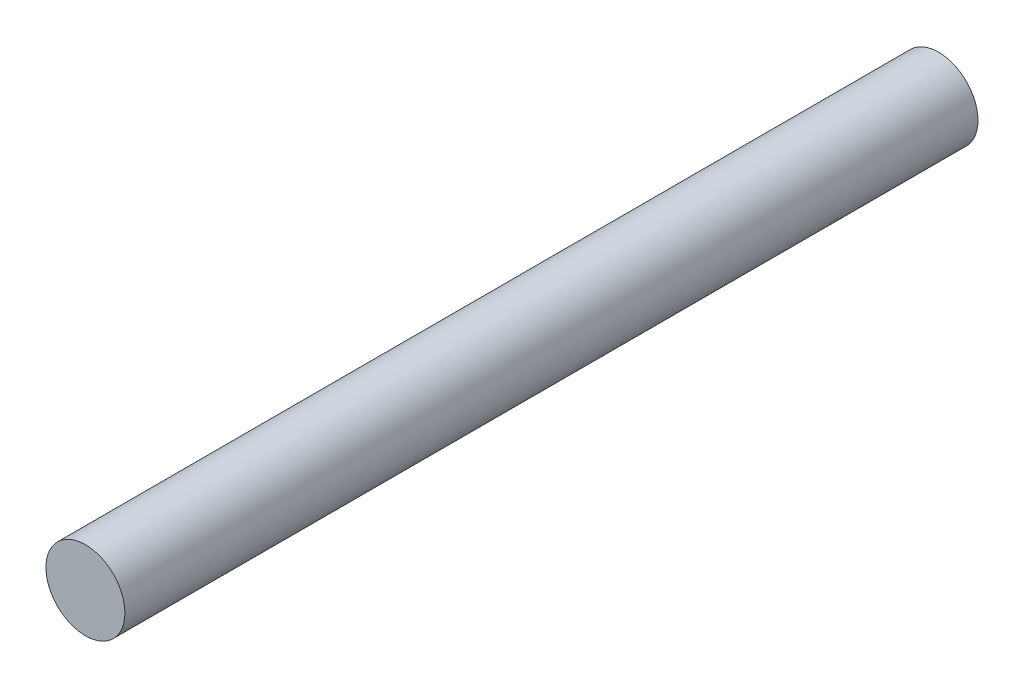
SolidWorks part; units mm, degrees
ref_plane "Front Plane" through (0, 0, 0) normal (0, 0, 1) x (1, 0, 0)
ref_plane "Top Plane" through (0, 0, 0) normal (0, 1, 0) x (1, 0, 0)
ref_plane "Right Plane" through (0, 0, 0) normal (1, 0, 0) x (0, 0, -1)
sketch "Sketch1" plane through (0, 0, 0) normal (0, 0, 1) x (1, 0, 0)
  circle A0 centre (0, 0) radius 2.5
  dimension "D1" = 5
extrude "Boss-Extrude1" add sketch "Sketch1" along normal blind 54
